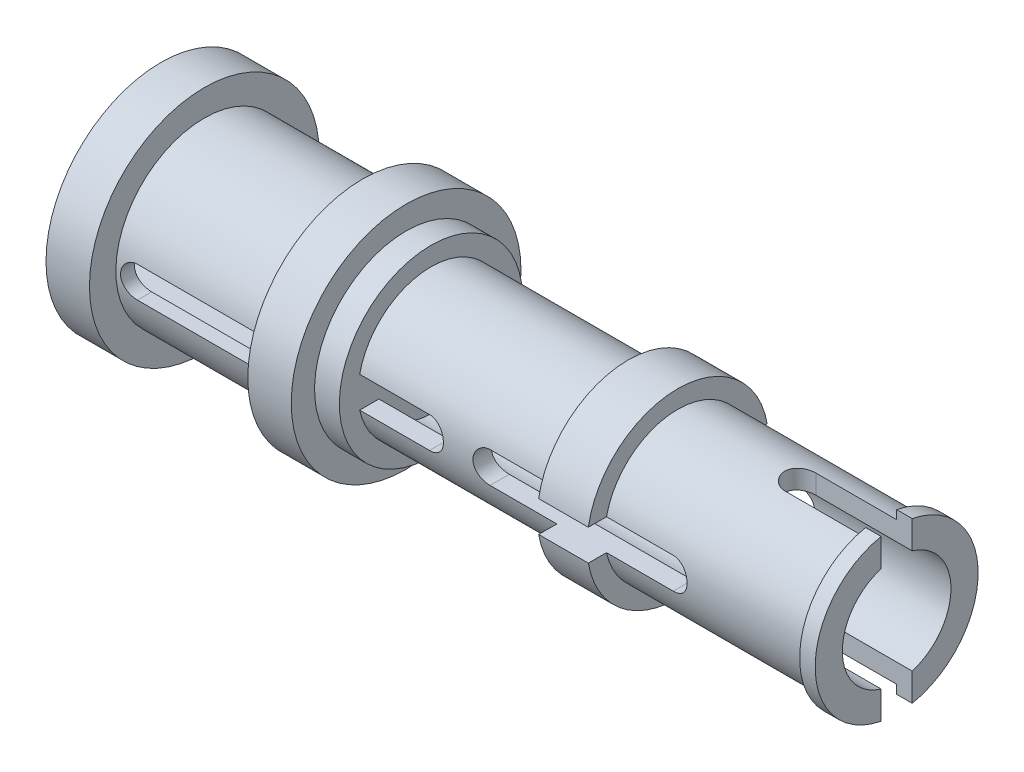
SolidWorks part; units mm, degrees
ref_plane "Front Plane" through (0, 0, 0) normal (0, 0, 1) x (1, 0, 0)
ref_plane "Top Plane" through (0, 0, 0) normal (0, 1, 0) x (1, 0, 0)
ref_plane "Right Plane" through (0, 0, 0) normal (1, 0, 0) x (0, 0, -1)
sketch "Sketch1" plane through (0, 0, 0) normal (1, 0, 0) x (0, 0, -1)
  circle A0 centre (0, 0) radius 1.75
  circle A1 centre (0, 0) radius 2.925
  dimension "D1" = 3.5
  dimension "D2" = 5.85
extrude "Middle Ring" add sketch "Sketch1" along normal mid plane 1.6
sketch "Sketch2" plane through (0, 0, 0) normal (1, 0, 0) x (0, 0, -1)
  circle A0 centre (0, 0) radius 1.75 construction
  circle A1 centre (0, 0) radius 1.75
  circle A2 centre (0, 0) radius 2.35
  dimension "D1" = 4.7
extrude "Outer Body" add sketch "Sketch2" along normal mid plane 14.7
sketch "Sketch3" plane through (7.35, 0, 0) normal (1, 0, 0) x (0, 0, -1)
  circle A0 centre (0, 0) radius 1.75 construction
  circle A1 centre (0, 0) radius 1.75
  circle A2 centre (0, 0) radius 2.625
  dimension "D1" = 5.25
extrude "Outer Rim" add sketch "Sketch3" along normal blind 0.5
mirror "Mirror1" about plane through (0, 0, 0) normal (1, 0, 0) of "Outer Rim"
sketch "Sketch4" plane through (0, 0, 0) normal (0, 0, 1) x (1, 0, 0)
  line L0 (2.95, 0) -> (-2.95, 0) construction
  line L1 (2.95, -0.5) -> (-2.95, -0.5)
  line L2 (2.95, 0.5) -> (-2.95, 0.5)
  line L3 (-10.8, 0) -> (-4.9, 0) construction
  line L4 (-7.85, 2.625) -> (-7.85, -2.625) construction
  line L5 (-10.8, 0.5) -> (-4.9, 0.5)
  line L6 (-10.8, -0.5) -> (-4.9, -0.5)
  arc A0 (2.95, -0.5) -> (2.95, 0.5) centre (2.95, 0) ccw
  arc A1 (-2.95, 0.5) -> (-2.95, -0.5) centre (-2.95, 0) ccw
  arc A2 (-10.8, 0.5) -> (-10.8, -0.5) centre (-10.8, 0) ccw
  arc A3 (-4.9, -0.5) -> (-4.9, 0.5) centre (-4.9, 0) ccw
  point P2 (0, 0)
  point P12 (-7.85, 0)
  dimension "D2" = 6.9
  dimension "D1" = 1
extrude "Middle Slot " cut sketch "Sketch4" against normal through all both and the other way through all
sketch "Sketch5" plane through (0, 0, 0) normal (0, 1, 0) x (1, 0, 0)
  line L0 (10.95, 0) -> (4.75, 0) construction
  line L1 (7.85, -2.625) -> (7.85, 2.625) construction
  line L2 (10.95, -0.5) -> (4.75, -0.5)
  line L3 (10.95, 0.5) -> (4.75, 0.5)
  line L4 (0, 0) -> (0, 3.8777) construction
  line L5 (-10.95, 0) -> (-4.75, 0) construction
  line L6 (-10.95, -0.5) -> (-4.75, -0.5) construction
  line L7 (-10.95, 0.5) -> (-4.75, 0.5) construction
  arc A0 (10.95, -0.5) -> (10.95, 0.5) centre (10.95, 0) ccw
  arc A1 (4.75, 0.5) -> (4.75, -0.5) centre (4.75, 0) ccw
  arc A2 (-10.95, -0.5) -> (-10.95, 0.5) centre (-10.95, 0) cw construction
  arc A3 (-4.75, 0.5) -> (-4.75, -0.5) centre (-4.75, 0) cw construction
  point P5 (7.85, 0)
  point P14 (-7.85, 0)
  dimension "D2" = 8.5
  dimension "D1" = 1
  dimension "D3" = 3.6
extrude "Side Slots" cut sketch "Sketch5" against normal through all both and the other way through all
sketch "Sketch6" plane through (0, 0, 0) normal (0, 0, 1) x (1, 0, 0)
  line L0 (0, 0) -> (-15.85, 0) construction
  line L1 (-15.85, 0) -> (-15.85, 3.7)
  line L2 (-15.85, 3.7) -> (-14.45, 3.7)
  line L3 (-14.45, 3.7) -> (-14.45, 2.85)
  line L4 (-14.45, 2.85) -> (-9.35, 2.85)
  line L5 (-9.35, 2.85) -> (-9.35, 3.7)
  line L6 (-9.35, 3.7) -> (-7.95, 3.7)
  line L7 (-7.95, 3.7) -> (-7.95, 2.95)
  line L8 (-7.95, 2.95) -> (-7.15, 2.95)
  line L9 (-7.15, 2.95) -> (-7.15, 0)
  line L10 (-7.15, 0) -> (-15.85, 0)
  line L11 (7.85, -2.5769) -> (7.85, 2.5769) construction
  dimension "D1" = 7.4
  dimension "D2" = 1.4
  dimension "D3" = 5.7
  dimension "D4" = 5.9
  dimension "D5" = 0.8
  dimension "D6" = 23.7
  dimension "D7" = 5.1
revolve "Large Bush" add sketch "Sketch6" angle 360 about L0
sketch "Sketch7" plane through (-15.85, 0, 0) normal (-1, 0, 0) x (0, 0, 1)
  line L1 (0.9, -2.4) -> (-0.9, -2.4)
  line L2 (0.9, -2.4) -> (0.9, 2.4)
  line L3 (0.9, 2.4) -> (-0.9, 2.4)
  line L4 (-0.9, -2.4) -> (-0.9, 2.4)
  line L5 (0.9, -2.4) -> (-0.9, 2.4) construction
  line L6 (0.9, 2.4) -> (-0.9, -2.4) construction
  line L7 (-2.4, -0.9) -> (2.4, -0.9)
  line L8 (-2.4, -0.9) -> (-2.4, 0.9)
  line L9 (-2.4, 0.9) -> (2.4, 0.9)
  line L10 (2.4, -0.9) -> (2.4, 0.9)
  line L11 (-2.4, -0.9) -> (2.4, 0.9) construction
  line L12 (-2.4, 0.9) -> (2.4, -0.9) construction
  circle A0 centre (0, 0) radius 2.4
  dimension "D1" = 4.8
  dimension "D2" = 1.8
extrude "Axle Cut " cut sketch "Sketch7" against normal up to surface (7.9 mm away) contours L2 A0 L4 L9 | L9 L4 L7 L2 | L9 A0 L7 L4 | A0 L9 L2 L7 | L4 A0 L2 L7 up to face at (-7.95, 3.7, 0)
sketch "Sketch9" plane through (0, 0, 0) normal (0, 0, 1) x (1, 0, 0)
  line L0 (-13.8, 0) -> (-10, 0) construction
  line L1 (-13.8, 0.5) -> (-10, 0.5)
  line L2 (-13.8, -0.5) -> (-10, -0.5)
  line L6 (-14.45, -3.7) -> (-14.45, 3.7) construction
  arc A0 (-13.8, 0.5) -> (-13.8, -0.5) centre (-13.8, 0) ccw
  arc A1 (-10, -0.5) -> (-10, 0.5) centre (-10, 0) ccw
  point P2 (-11.9, 0)
  dimension "D1" = 4.8
  dimension "D2" = 1
  dimension "D3" = 2.55
extrude "Bush Slot " cut sketch "Sketch9" against normal through all both and the other way through all
